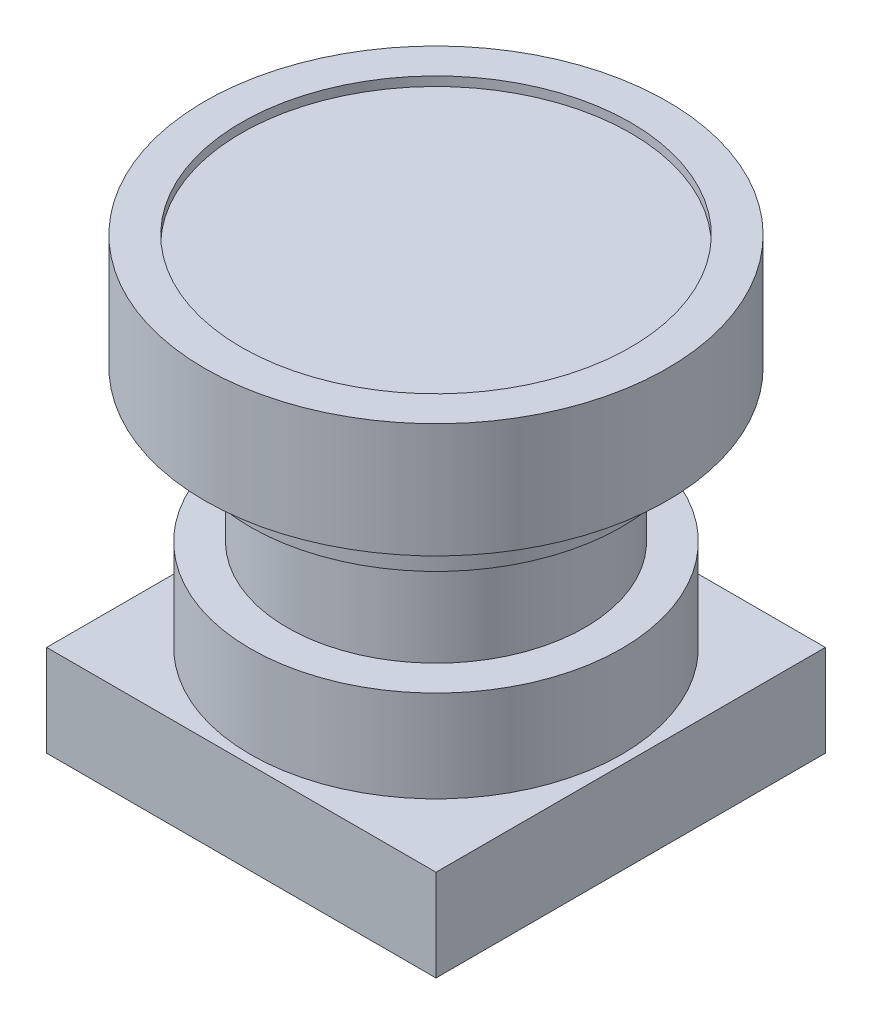
SolidWorks part; units mm, degrees
ref_plane "Front Plane" through (0, 0, 0) normal (0, 0, 1) x (1, 0, 0)
ref_plane "Top Plane" through (0, 0, 0) normal (0, 1, 0) x (1, 0, 0)
ref_plane "Right Plane" through (0, 0, 0) normal (1, 0, 0) x (0, 0, -1)
sketch "Sketch1" plane through (0, 0, 0) normal (0, 1, 0) x (1, 0, 0)
  line L0 (-4.25, 0) -> (4.25, 0) construction
  line L1 (-4.25, 4.25) -> (4.25, 4.25)
  line L2 (-4.25, 4.25) -> (-4.25, -4.25)
  line L3 (-4.25, -4.25) -> (4.25, -4.25)
  line L4 (4.25, 4.25) -> (4.25, -4.25)
  point P6 (0, 0)
  dimension "D1" = 8.5
extrude "Boss-Extrude1" add sketch "Sketch1" along normal blind 2
sketch "Sketch2" plane through (0, 2, 0) normal (0, 1, 0) x (1, 0, 0)
  line L0 (4.25, 4.25) -> (-4.25, 4.25) construction
  circle A0 centre (0, 0) radius 4.25 construction
  circle A1 centre (0, 0) radius 4.05
  circle A2 centre (0, 0) radius 3.25
  dimension "D1" = 0.2
  dimension "D2" = 0.8
extrude "Boss-Extrude2" add sketch "Sketch2" along normal blind 2
sketch "Sketch3" plane through (0, 2, 0) normal (0, 1, 0) x (1, 0, 0)
  circle A0 centre (0, 0) radius 3.25 construction
  circle A1 centre (0, 0) radius 3.25
extrude "Boss-Extrude3" add sketch "Sketch3" along normal blind 4.3
sketch "Sketch4" plane through (0, 6.3, 0) normal (0, 1, 0) x (1, 0, 0)
  circle A0 centre (0, 0) radius 4.05 construction
  circle A1 centre (0, 0) radius 4.05
extrude "Boss-Extrude4" add sketch "Sketch4" along normal blind 1
sketch "Sketch5" plane through (0, 7.3, 0) normal (0, 1, 0) x (1, 0, 0)
  circle A2 centre (0, 0) radius 5.05
  circle A3 centre (0, 0) radius 5.05
  dimension "D1" = 1
extrude "Boss-Extrude5" add sketch "Sketch5" along normal blind 2.5
sketch "Sketch6" plane through (0, 9.8, 0) normal (0, 1, 0) x (1, 0, 0)
  circle A2 centre (0, 0) radius 4.25
  circle A3 centre (0, 0) radius 4.25
  dimension "D1" = 0.8
extrude "Cut-Extrude1" cut sketch "Sketch6" against normal blind 0.2
